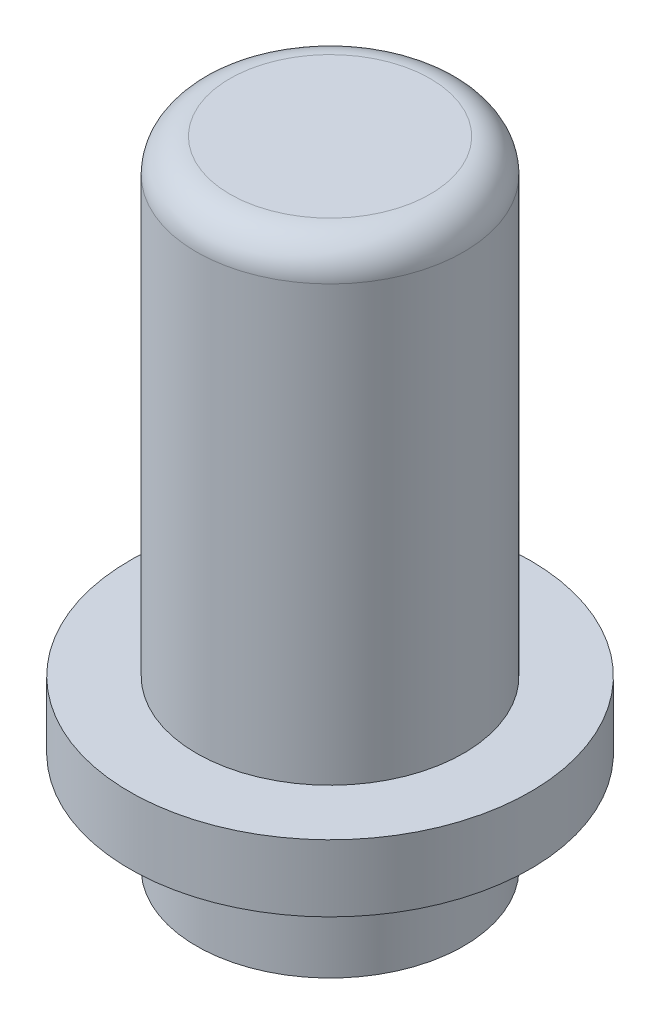
SolidWorks part; units mm, degrees
ref_plane "前视基准面" through (0, 0, 0) normal (0, 0, 1) x (1, 0, 0)
ref_plane "上视基准面" through (0, 0, 0) normal (0, 1, 0) x (1, 0, 0)
ref_plane "右视基准面" through (0, 0, 0) normal (1, 0, 0) x (0, 0, -1)
sketch "草图1" plane through (0, 0, 0) normal (0, 1, 0) x (1, 0, 0)
  circle A0 centre (0, 0) radius 2
  dimension "D1" = 4
extrude "凸台-拉伸1" add sketch "草图1" along normal blind 7
fillet "圆角2" radius 0.5 1 edges at (0, 7, 2)
sketch "草图4" plane through (0, 0, 0) normal (0, -1, 0) x (1, 0, 0)
  circle A0 centre (0, 0) radius 3
  dimension "D1" = 6
extrude "凸台-拉伸2" add sketch "草图4" along normal blind 1
sketch "草图5" plane through (0, -1, 0) normal (0, -1, 0) x (1, 0, 0)
  circle A0 centre (0, 0) radius 2
  dimension "D1" = 4
extrude "凸台-拉伸3" add sketch "草图5" along normal blind 1.5
sketch "草图6" plane through (0, -2.5, 0) normal (0, -1, 0) x (1, 0, 0)
  line L1 (1.7321, 0) -> (0.866, 1.5)
  line L2 (0.866, 1.5) -> (-0.866, 1.5)
  line L3 (-0.866, 1.5) -> (-1.7321, 0)
  line L4 (-1.7321, 0) -> (-0.866, -1.5)
  line L5 (-0.866, -1.5) -> (0.866, -1.5)
  line L6 (0.866, -1.5) -> (1.7321, 0)
  circle A0 centre (0, 0) radius 1.5 construction
  dimension "D1" = 3
extrude "切除-拉伸1" cut sketch "草图6" against normal blind 2 contours L2 L3 L4 L5 L6 L1
